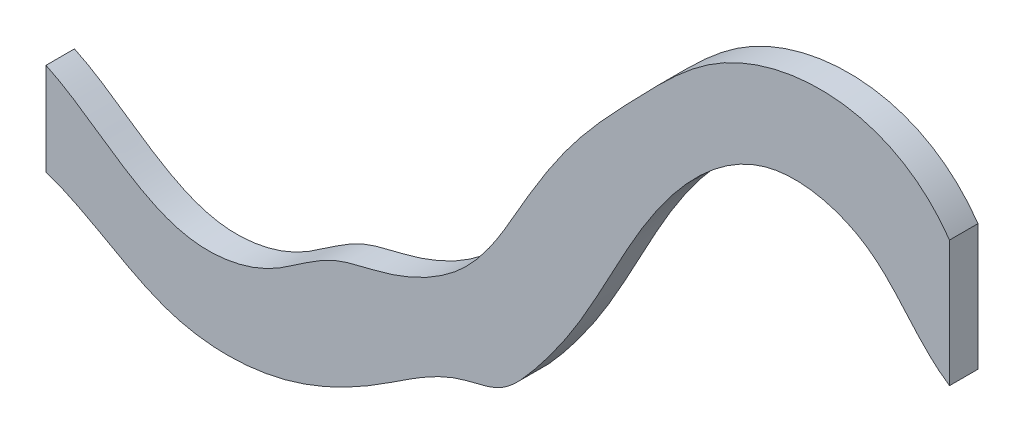
SolidWorks part; units mm, degrees
ref_plane "Front Plane" through (0, 0, 0) normal (0, 0, 1) x (1, 0, 0)
ref_plane "Top Plane" through (0, 0, 0) normal (0, 1, 0) x (1, 0, 0)
ref_plane "Right Plane" through (0, 0, 0) normal (1, 0, 0) x (0, 0, -1)
sketch "Sketch1" plane through (0, 0, 0) normal (0, 0, 1) x (1, 0, 0)
  line L0 (0, 7.874) -> (0, 18.1102)
  line L1 (100, 51.3601) -> (100, 37.4016)
  spline S0 degree 3 poles (0, 7.874) (4.9446, 6.2439) (10.4758, 1.5602) (19.801, 0.0784) (28.0456, 1.0231) (36.9054, 5.6248) (44.0023, 10.934) (50.4227, 11.835) (54.5546, 16.3692) (59.4752, 23.2282) (64.1435, 32.715) (70.2597, 42.4494) (79.6499, 50.1463) (92.6826, 46.9489) (96.4461, 39.7132) (100, 37.4016) knots 0 0 0 0 0.124881 0.163042 0.222969 0.319803 0.39841 0.431158 0.46893 0.538577 0.635461 0.718984 0.816425 0.900124 1 1 1 1
  spline S1 degree 3 poles (0, 18.1102) (5.1973, 15.6811) (12.5012, 7.7449) (25.0979, 10.2326) (30.8311, 15.6468) (38.8396, 16.9234) (47.53, 21.4372) (52.5951, 31.302) (58.5356, 40.5274) (65.918, 48.2338) (77.6815, 60.2702) (93.8349, 60.2243) (100, 51.3601) knots 0 0 0 0 0.148942 0.220352 0.28772 0.334218 0.414249 0.515237 0.595839 0.681769 0.774601 1 1 1 1
extrude "Boss-Extrude1" add sketch "Sketch1" along normal blind 3.15
